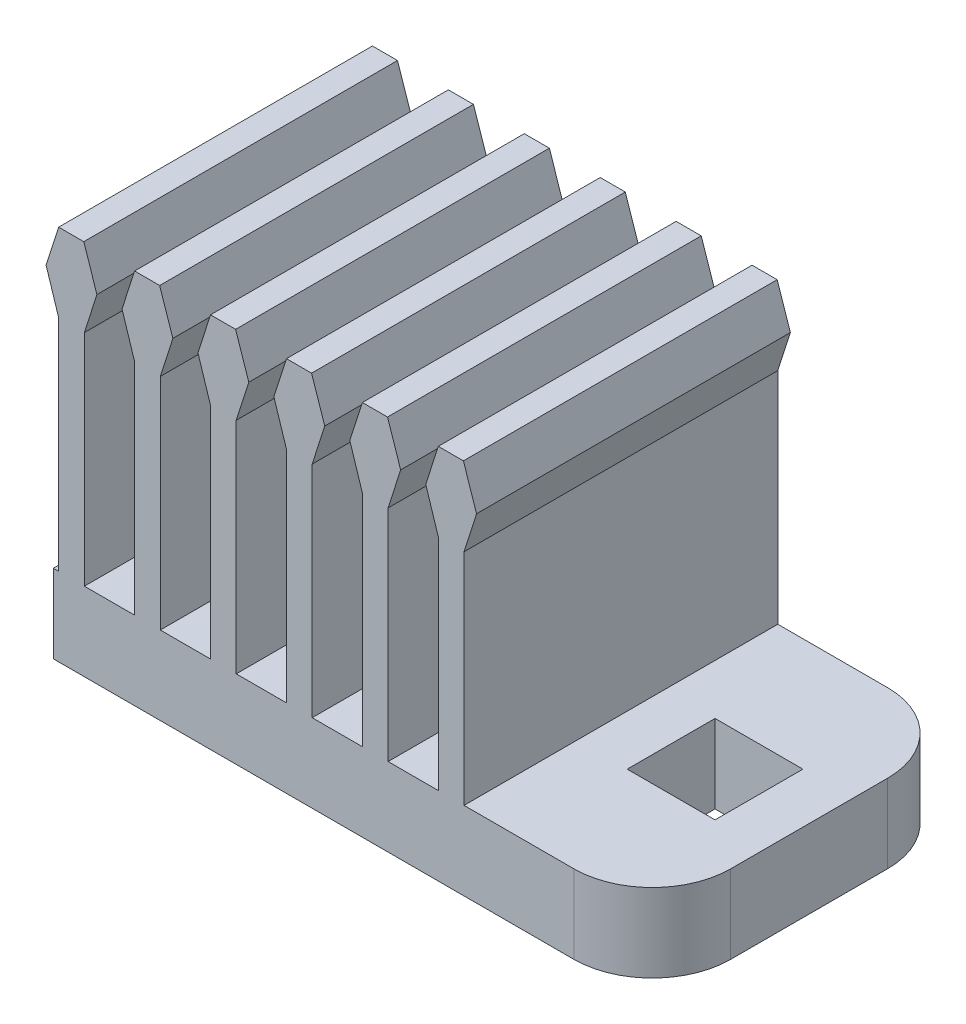
SolidWorks part; units mm, degrees
ref_plane "Plano frontal" through (0, 0, 0) normal (0, 0, 1) x (1, 0, 0)
ref_plane "Plano superior" through (0, 0, 0) normal (0, 1, 0) x (1, 0, 0)
ref_plane "Plano direito" through (0, 0, 0) normal (1, 0, 0) x (0, 0, -1)
sketch "Esboço1" plane through (0, 0, 0) normal (0, 0, 1) x (1, 0, 0)
  line L0 (-0.4, 0) -> (-0.57, 0)
  line L1 (0, 0) -> (0, 7) construction
  line L2 (0, 0) -> (0, 7) construction
  line L3 (5.26, 0) -> (6.86, 0)
  line L4 (-0.4, 7) -> (-0.4, 0)
  line L5 (0.42, 7) -> (0.42, 0)
  line L6 (0.42, 0) -> (2.02, 0)
  line L7 (2.02, 7) -> (2.02, 0)
  line L8 (-0.57, -2.5) -> (5.43, -2.5)
  line L9 (6.86, 7) -> (6.86, 0)
  line L10 (7.68, 7) -> (7.68, 0)
  line L11 (7.68, 7) -> (8.08, 8.25)
  line L12 (6.86, 9.5) -> (7.66, 9.5)
  line L13 (7.66, 9.5) -> (8.08, 8.25)
  line L14 (2.84, 7) -> (2.84, 0)
  line L15 (2.84, 0) -> (4.44, 0)
  line L16 (2.84, 7) -> (3.24, 8.25)
  line L17 (2.02, 9.5) -> (2.82, 9.5)
  line L18 (2.82, 9.5) -> (3.24, 8.25)
  line L19 (2.02, 7) -> (1.62, 8.25)
  line L20 (2.02, 9.5) -> (1.62, 8.25)
  line L21 (2.43, 0) -> (2.43, 7) construction
  line L22 (2.43, 7) -> (2.84, 7) construction
  line L23 (2.43, 7) -> (2.02, 7) construction
  line L24 (6.86, 7) -> (6.46, 8.25)
  line L25 (-0.57, -2.5) -> (-0.57, 0)
  line L26 (0, 7) -> (0.42, 7) construction
  line L27 (0, 7) -> (-0.4, 7) construction
  line L28 (0.42, 7) -> (0.82, 8.25)
  line L29 (-0.4, 9.5) -> (0.4, 9.5)
  line L30 (0.4, 9.5) -> (0.82, 8.25)
  line L31 (-0.4, 7) -> (-0.8, 8.25)
  line L32 (-0.4, 9.5) -> (-0.8, 8.25)
  line L33 (6.86, 9.5) -> (6.46, 8.25)
  line L34 (4.44, 7) -> (4.44, 0)
  line L35 (5.26, 7) -> (5.26, 0)
  line L36 (7.26, 0) -> (7.26, 7) construction
  line L37 (5.26, 7) -> (5.66, 8.25)
  line L38 (4.44, 9.5) -> (5.24, 9.5)
  line L39 (5.24, 9.5) -> (5.66, 8.25)
  line L40 (7.26, 7) -> (7.68, 7) construction
  line L41 (7.26, 7) -> (6.86, 7) construction
  line L42 (4.44, 7) -> (4.04, 8.25)
  line L43 (4.44, 9.5) -> (4.04, 8.25)
  line L44 (4.84, 0) -> (4.84, 7) construction
  line L45 (4.84, 7) -> (5.26, 7) construction
  line L46 (4.84, 7) -> (4.44, 7) construction
  line L47 (7.68, 0) -> (9.28, 0)
  line L48 (9.28, 7) -> (9.28, 0)
  line L49 (10.1, 7) -> (10.1, 0)
  line L50 (10.1, 7) -> (10.5, 8.25)
  line L51 (9.28, 9.5) -> (10.08, 9.5)
  line L52 (10.08, 9.5) -> (10.5, 8.25)
  line L53 (9.28, 7) -> (8.88, 8.25)
  line L54 (9.28, 9.5) -> (8.88, 8.25)
  line L55 (9.68, 0) -> (9.68, 7) construction
  line L56 (9.68, 7) -> (10.1, 7) construction
  line L57 (9.68, 7) -> (9.28, 7) construction
  line L58 (10.1, 0) -> (11.7, 0)
  line L59 (11.7, 7) -> (11.7, 0)
  line L60 (12.52, 7) -> (12.52, 0)
  line L61 (12.52, 7) -> (12.92, 8.25)
  line L62 (11.7, 9.5) -> (12.5, 9.5)
  line L63 (12.5, 9.5) -> (12.92, 8.25)
  line L64 (11.7, 7) -> (11.3, 8.25)
  line L65 (11.7, 9.5) -> (11.3, 8.25)
  line L66 (12.1, 0) -> (12.1, 7) construction
  line L67 (12.1, 7) -> (12.52, 7) construction
  line L68 (12.1, 7) -> (11.7, 7) construction
  line L69 (12.52, 0) -> (18.52, 0)
  line L70 (18.52, 0) -> (18.52, -2.5)
  line L71 (18.52, -2.5) -> (5.43, -2.5)
  point P4 (2, 12)
  point P32 (2.43, -2.5)
  dimension "D4" = 3
  dimension "D5" = 0.82
  dimension "D6" = 0.82
  dimension "D7" = 1.6
  dimension "D8" = 1.6
  dimension "D9" = 0.82
extrude "Ressalto-extrusão1" add sketch "Esboço1" along normal blind 10
sketch "Esboço2" plane through (0, 0, 0) normal (0, 1, 0) x (1, 0, 0)
  line L0 (18.52, -5) -> (12.52, -5) construction
  line L1 (18.52, -10) -> (18.52, 0) construction
  line L4 (14.12, -3.6) -> (16.92, -3.6)
  line L5 (14.12, -3.6) -> (14.12, -6.4)
  line L6 (14.12, -6.4) -> (16.92, -6.4)
  line L7 (16.92, -3.6) -> (16.92, -6.4)
  line L8 (14.12, -3.6) -> (16.92, -6.4) construction
  line L9 (14.12, -6.4) -> (16.92, -3.6) construction
  line L12 (18.52, -7.5) -> (18.52, -2.5)
  line L14 (16.02, -10) -> (18.52, -10)
  line L15 (18.52, -10) -> (18.52, -7.5)
  line L16 (18.52, -2.5) -> (18.52, 0)
  line L17 (18.52, 0) -> (16.02, 0)
  arc A0 (16.02, -10) -> (18.52, -7.5) centre (16.02, -7.5) ccw
  arc A1 (18.52, -2.5) -> (16.02, 0) centre (16.02, -2.5) ccw
  point P4 (15.52, -5)
  point P5 (15.52, -5)
  line M1 (18.52, 0) -> (12.52, 0)
  line M3 (12.52, -10) -> (18.52, -10)
  line M4 (18.52, -10) -> (18.52, 0)
  dimension "D2" = 2.5
  dimension "D1" = 2.8
extrude "Corte-extrusão1" cut sketch "Esboço2" against normal through all contours L7 L4 L5 L6 | A1 M4 M1 | A0 M3 M4
